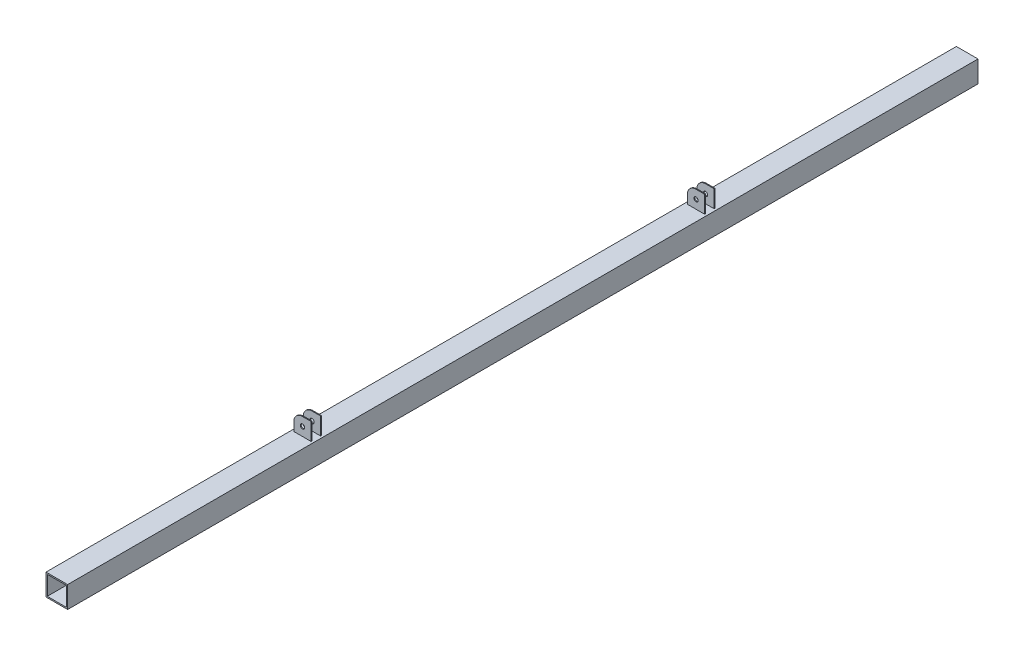
SolidWorks part; units mm, degrees
ref_plane "Front Plane" through (0, 0, 0) normal (0, 0, 1) x (1, 0, 0)
ref_plane "Top Plane" through (0, 0, 0) normal (0, 1, 0) x (1, 0, 0)
ref_plane "Right Plane" through (0, 0, 0) normal (1, 0, 0) x (0, 0, -1)
sketch "Sketch3" plane through (0, 0, 0) normal (0, 0, 1) x (1, 0, 0)
  line L1 (-25, -25) -> (25, -25)
  line L2 (-25, -25) -> (-25, 25)
  line L3 (-25, 25) -> (25, 25)
  line L4 (25, -25) -> (25, 25)
  line L5 (-25, -25) -> (25, 25) construction
  line L6 (-25, 25) -> (25, -25) construction
  line L7 (-22, -22) -> (22, -22)
  line L8 (-22, -22) -> (-22, 22)
  line L9 (-22, 22) -> (22, 22)
  line L10 (22, -22) -> (22, 22)
  line L11 (-22, -22) -> (22, 22) construction
  line L12 (-22, 22) -> (22, -22) construction
  point P0 (0, 0)
  point P7 (0, 0)
  dimension "D1" = 50
  dimension "D2" = 50
  dimension "D3" = 3
  dimension "D4" = 3
extrude "Boss-Extrude1" add sketch "Sketch3" along normal mid plane 2105
sketch "Sketch4" plane through (0, 25, 0) normal (0, 1, 0) x (1, 0, 0)
  line L0 (0, 447.5) -> (0, 427.5) construction
  line L17 (25, -1052.5) -> (-25, -1052.5) construction
  line L20 (-20, 449.5) -> (20, 449.5)
  line L21 (-20, 449.5) -> (-20, 447.5)
  line L22 (-20, 447.5) -> (20, 447.5)
  line L23 (20, 449.5) -> (20, 447.5)
  line L24 (-20, 427.5) -> (20, 427.5)
  line L25 (-20, 427.5) -> (-20, 425.5)
  line L26 (-20, 425.5) -> (20, 425.5)
  line L27 (20, 427.5) -> (20, 425.5)
  line L28 (-20, -460.5) -> (20, -460.5)
  line L29 (-20, -460.5) -> (-20, -462.5)
  line L30 (-20, -462.5) -> (20, -462.5)
  line L31 (20, -460.5) -> (20, -462.5)
  line L32 (-20, -482.5) -> (20, -482.5)
  line L33 (-20, -482.5) -> (-20, -484.5)
  line L34 (-20, -484.5) -> (20, -484.5)
  line L35 (20, -482.5) -> (20, -484.5)
  line L36 (0, -462.5) -> (0, -482.5) construction
  line L39 (25, -1052.5) -> (25, 1052.5) construction
  dimension "D1" = 40
  dimension "D2" = 2
  dimension "D3" = 20
  dimension "D4" = 570
  dimension "D5" = 1480
  dimension "D6" = 20
  dimension "D7" = 25
extrude "Boss-Extrude2" add sketch "Sketch4" along normal blind 40
sketch "Sketch5" plane through (0, 0, 484.5) normal (0, 0, 1) x (1, 0, 0)
  line L0 (-20, 65) -> (20, 65) construction
  line L2 (20, 65) -> (20, 25) construction
  circle A0 centre (0, 45) radius 5
  dimension "D1" = 10
  dimension "D2" = 20
  dimension "D3" = 20
extrude "Cut-Extrude1" cut sketch "Sketch5" against normal blind 1000
fillet "Fillet1" radius 20 4 edges at (-20, 65, 483.5) (-20, 65, 461.5) (-20, 65, -426.5) (-20, 65, -448.5)
